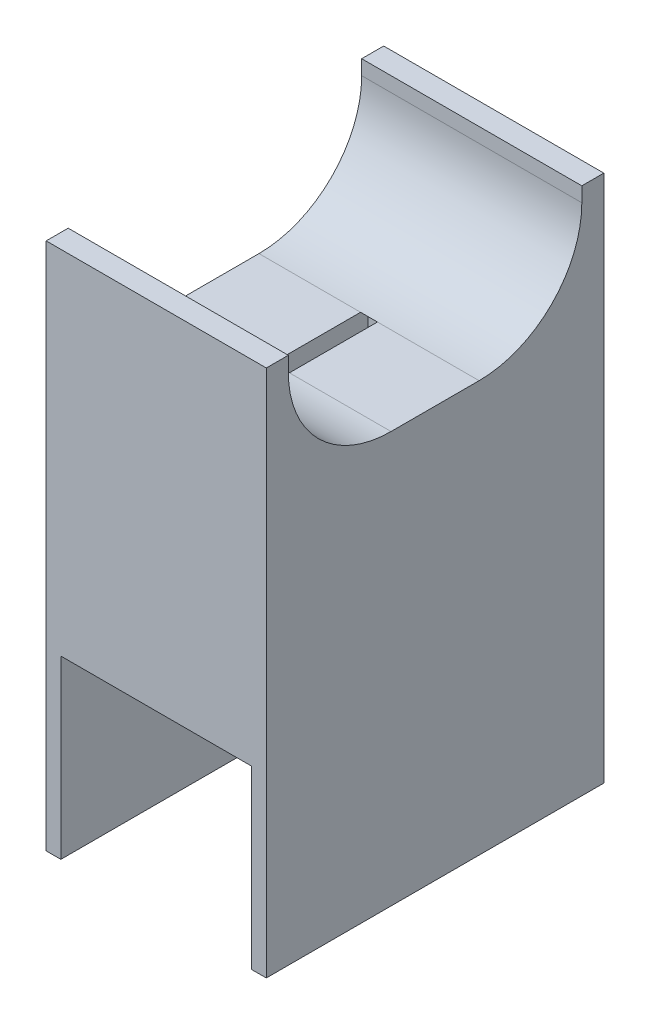
SolidWorks part; units mm, degrees
ref_plane "Front Plane" through (0, 0, 0) normal (0, 0, 1) x (1, 0, 0)
ref_plane "Top Plane" through (0, 0, 0) normal (0, 1, 0) x (1, 0, 0)
ref_plane "Right Plane" through (0, 0, 0) normal (1, 0, 0) x (0, 0, -1)
sketch "Sketch1" plane through (0, 0, 0) normal (0, 1, 0) x (1, 0, 0)
  line L1 (-7.5, -11.5) -> (7.5, -11.5)
  line L2 (-7.5, -11.5) -> (-7.5, 11.5)
  line L3 (-7.5, 11.5) -> (7.5, 11.5)
  line L4 (7.5, -11.5) -> (7.5, 11.5)
  line L5 (-7.5, -11.5) -> (7.5, 11.5) construction
  line L6 (-7.5, 11.5) -> (7.5, -11.5) construction
  point P0 (0, 0)
  dimension "D1" = 23
  dimension "D2" = 15
extrude "Boss-Extrude1" add sketch "Sketch1" along normal blind 26
sketch "Sketch4" plane through (7.5, 0, 0) normal (1, 0, 0) x (0, 0, -1)
  line L3 (-11.5, 26) -> (11.5, 26) construction
  line L4 (-10, 26) -> (10, 26)
  line L5 (-10, 26) -> (-10, 18)
  line L6 (-10, 18) -> (10, 18)
  line L7 (10, 26) -> (10, 18)
  line L8 (-11.5, 26) -> (-11.5, 0) construction
  line L9 (11.5, 26) -> (11.5, 0) construction
  dimension "D1" = 1.5
  dimension "D2" = 1.5
  dimension "D3" = 8
extrude "Cut-Extrude2" cut sketch "Sketch4" against normal through all
fillet "Fillet1" radius 7 2 edges at (0, 18, -10) (0, 18, 10)
sketch "Sketch5" plane through (0, 0, 0) normal (0, -1, 0) x (1, 0, 0)
  line L1 (-7.5, -11.5) -> (7.5, -11.5)
  line L2 (-7.5, -11.5) -> (-7.5, 11.5)
  line L3 (-7.5, 11.5) -> (7.5, 11.5)
  line L4 (7.5, -11.5) -> (7.5, 11.5)
  line L5 (-7.5, -11.5) -> (7.5, 11.5) construction
  line L6 (-7.5, 11.5) -> (7.5, -11.5) construction
  point P0 (0, 0)
extrude "Boss-Extrude2" add sketch "Sketch5" along normal blind 10
sketch "Sketch7" plane through (0, 0, 11.5) normal (0, 0, 1) x (1, 0, 0)
  line L0 (7.5, -10) -> (-7.5, -10) construction
  line L1 (-6.5, -10) -> (6.5, -10)
  line L2 (-6.5, -10) -> (-6.5, 2)
  line L3 (-6.5, 2) -> (6.5, 2)
  line L4 (6.5, -10) -> (6.5, 2)
  line L5 (-7.5, 26) -> (-7.5, -10) construction
  line L6 (7.5, 26) -> (7.5, -10) construction
  dimension "D1" = 1
  dimension "D2" = 1
  dimension "D3" = 12
extrude "Cut-Extrude3" cut sketch "Sketch7" against normal through all
sketch "Sketch11" plane through (0, 2, 0) normal (0, -1, 0) x (1, 0, 0)
  line L1 (-0.575, -3.5) -> (0.575, -3.5)
  line L2 (-0.575, -3.5) -> (-0.575, 3.5)
  line L3 (-0.575, 3.5) -> (0.575, 3.5)
  line L4 (0.575, -3.5) -> (0.575, 3.5)
  line L5 (-0.575, -3.5) -> (0.575, 3.5) construction
  line L6 (-0.575, 3.5) -> (0.575, -3.5) construction
  point P0 (0, 0)
  dimension "D1" = 7
  dimension "D2" = 1.15
extrude "Cut-Extrude4" cut sketch "Sketch11" against normal blind 16
